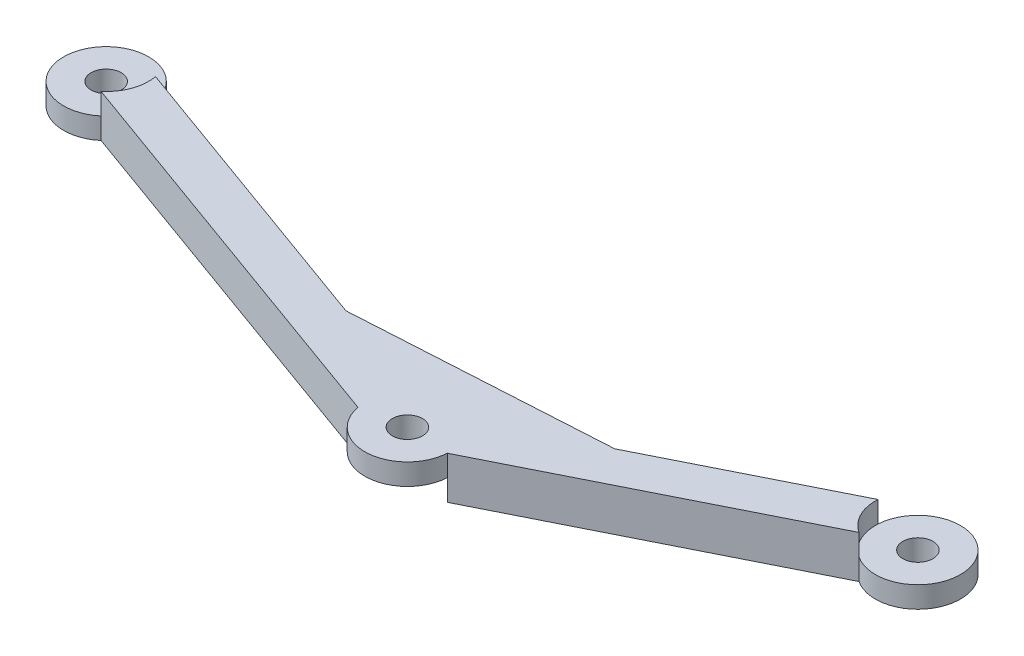
SolidWorks part; units mm, degrees
ref_plane "Front Plane" through (0, 0, 0) normal (0, 0, 1) x (1, 0, 0)
ref_plane "Top Plane" through (0, 0, 0) normal (0, 1, 0) x (1, 0, 0)
ref_plane "Right Plane" through (0, 0, 0) normal (1, 0, 0) x (0, 0, -1)
sketch "Sketch2" plane through (0, 0, 0) normal (0, 1, 0) x (1, 0, 0)
  line L0 (0, 0) -> (70.358, -25.4)
  line L1 (70.358, -25.4) -> (71.4361, -22.4136)
  line L2 (71.4361, -22.4136) -> (6.2506, 1.119)
  line L3 (69.2799, -28.3864) -> (4.0944, -4.8537)
  line L4 (70.358, -25.4) -> (121.158, 0)
  line L5 (121.158, 0) -> (119.7381, 2.8398)
  line L6 (119.7381, 2.8398) -> (73.8568, -20.1008)
  line L7 (122.5779, -2.8398) -> (76.6966, -25.7805)
  circle A0 centre (0, 0) radius 2.2479
  circle A1 centre (0, 0) radius 3.175
  circle A2 centre (0, 0) radius 6.35
  circle A9 centre (121.158, 0) radius 2.2479
  circle A10 centre (121.158, 0) radius 3.175
  circle A11 centre (121.158, 0) radius 6.35
  circle A12 centre (70.358, -25.4) radius 2.2479
  circle A13 centre (70.358, -25.4) radius 3.175
  circle A14 centre (70.358, -25.4) radius 6.35
  dimension "D1" = 4.4958
  dimension "D2" = 6.35
  dimension "D3" = 12.7
  dimension "D4" = 4.4958
  dimension "D5" = 6.35
  dimension "D6" = 12.7
  dimension "D7" = 4.4958
  dimension "D8" = 6.35
  dimension "D9" = 12.7
  dimension "D10" = 121.158
  dimension "D11" = 50.8
  dimension "D12" = 25.4
extrude "Boss-Extrude2" add sketch "Sketch2" along normal blind 6.35
sketch "Sketch3" plane through (0, 6.35, 0) normal (0, 1, 0) x (1, 0, 0)
  circle A0 centre (0, 0) radius 6.35
  circle A1 centre (121.158, 0) radius 6.35
extrude "Cut-Extrude1" cut sketch "Sketch3" against normal blind 3.175
sketch "Sketch4" plane through (0, 0, 0) normal (0, -1, 0) x (1, 0, 0)
  circle A0 centre (70.358, 25.4) radius 6.35
extrude "Cut-Extrude2" cut sketch "Sketch4" against normal blind 3.175
sketch "Sketch5" plane through (0, 6.35, 0) normal (0, 1, 0) x (1, 0, 0)
  line L0 (88.6238, -12.7174) -> (73.8568, -20.1008)
  line L1 (114.8194, 0.3805) -> (73.8568, -20.1008) construction
  line L2 (50.7345, -14.9402) -> (66.2636, -20.5463)
  line L3 (66.2636, -20.5463) -> (6.2506, 1.119) construction
  line L6 (50.7345, -14.9402) -> (88.6238, -12.7174)
  arc A0 (73.8568, -20.1008) -> (66.2636, -20.5463) centre (70.358, -25.4) ccw
  dimension "D1" = 16.51
  dimension "D2" = 16.51
extrude "Boss-Extrude3" add sketch "Sketch5" against normal blind 6.35
